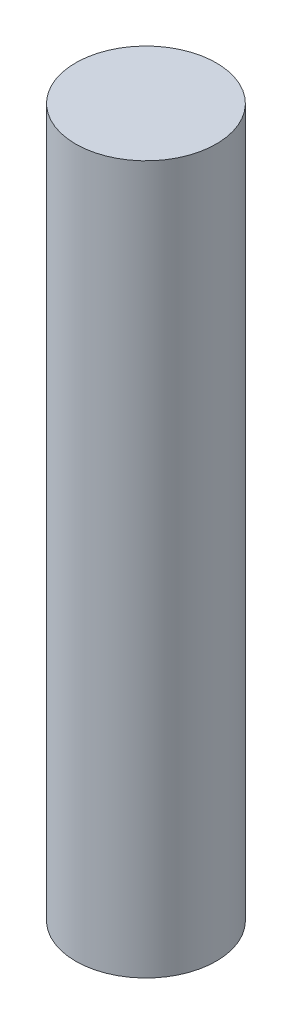
SolidWorks part; units mm, degrees
ref_plane "Front Plane" through (0, 0, 0) normal (0, 0, 1) x (1, 0, 0)
ref_plane "Top Plane" through (0, 0, 0) normal (0, 1, 0) x (1, 0, 0)
ref_plane "Right Plane" through (0, 0, 0) normal (1, 0, 0) x (0, 0, -1)
sketch "Sketch1" plane through (0, 0, 0) normal (0, 1, 0) x (1, 0, 0)
  circle A0 centre (0, 0) radius 0.795
extrude "Boss-Extrude1" add sketch "Sketch1" along normal blind 8
